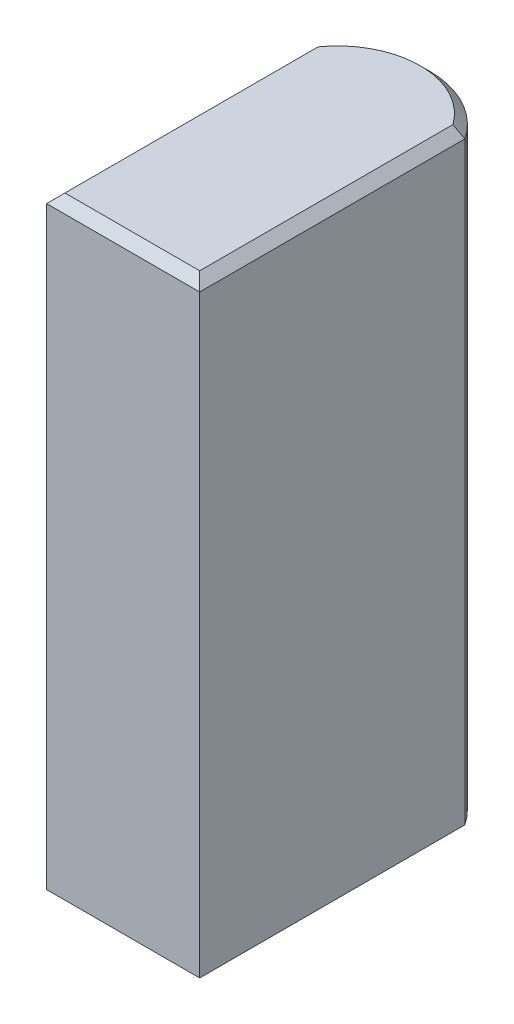
SolidWorks part; units mm, degrees
material "AISI 1045 Steel, cold drawn"
ref_plane "Front Plane" through (0, 0, 0) normal (0, 0, 1) x (1, 0, 0)
ref_plane "Top Plane" through (0, 0, 0) normal (0, 1, 0) x (1, 0, 0)
ref_plane "Right Plane" through (0, 0, 0) normal (1, 0, 0) x (0, 0, -1)
sketch "Sketch1" plane through (0, 0, 0) normal (0, 1, 0) x (1, 0, 0)
  line L0 (-4.9591, 10) -> (6.6809, 10) construction
  line L1 (2.5, 0) -> (-2.5, 0)
  line L2 (2.5, 0) -> (2.5, 8.6583)
  line L4 (-2.5, 0) -> (-2.5, 8.6583)
  arc A0 (-2.5, 8.6583) -> (2.5, 8.6583) centre (0, 7) cw
  point P0 (0, 0)
  dimension "D2" = 3
  dimension "D3" = 10
  dimension "D1" = 5
extrude "Boss-Extrude1" add sketch "Sketch1" along normal blind 20
chamfer "Chamfer1" distance 0.3 angle 45 8 edges at (-2.5, 0, -4.3292) (0, 0, 0) (2.5, 0, -4.3292) (0, 0, -10) (2.5, 20, -4.3292) (0, 20, 0) (-2.5, 20, -4.3292) (0, 20, -10)
